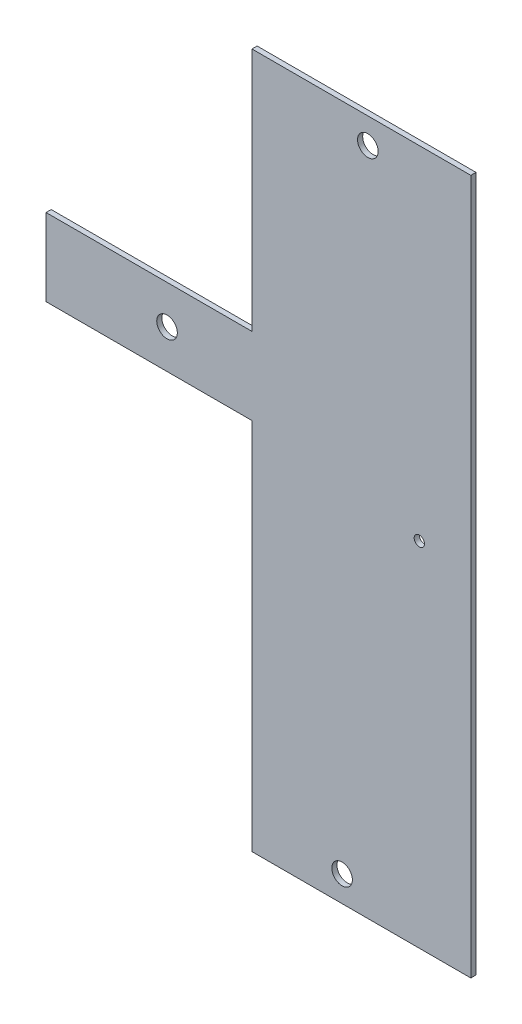
SolidWorks part; units mm, degrees
ref_plane "Front Plane" through (0, 0, 0) normal (0, 0, 1) x (1, 0, 0)
ref_plane "Top Plane" through (0, 0, 0) normal (0, 1, 0) x (1, 0, 0)
ref_plane "Right Plane" through (0, 0, 0) normal (1, 0, 0) x (0, 0, -1)
sketch "Sketch2" plane through (0, 0, 0) normal (0, 0, 1) x (1, 0, 0)
  line L0 (-70.0488, 14.6032) -> (9.9512, 14.6032)
  line L1 (9.9512, 14.6032) -> (9.9512, 109.6032)
  line L2 (9.9512, 109.6032) -> (94.9512, 109.6032)
  line L3 (94.9512, 109.6032) -> (94.9512, -160.3968)
  line L4 (94.9512, -160.3968) -> (9.9512, -160.3968)
  line L5 (9.9512, -160.3968) -> (9.9512, -15.3968)
  line L6 (9.9512, -15.3968) -> (-70.0488, -15.3968)
  line L7 (-70.0488, -15.3968) -> (-70.0488, 14.6032)
  dimension "D1" = 10
  dimension "D2" = 40
  dimension "D3" = 10
  dimension "D4" = 45
  dimension "D5" = 95
  dimension "D6" = 30
  dimension "D7" = 80
extrude "Extrude2" add sketch "Sketch2" along normal blind 2
sketch "Sketch3" plane through (0, 0, 0) normal (0, 0, -1) x (-1, 0, 0)
  circle A0 centre (-54.9512, 99.6032) radius 4
  circle A1 centre (23.0488, -0.3968) radius 4
  circle A2 centre (-74.9513, -23.3968) radius 2
  circle A3 centre (-44.9512, -150.3968) radius 4
extrude "Cut-Extrude1" cut sketch "Sketch3" against normal blind 2
